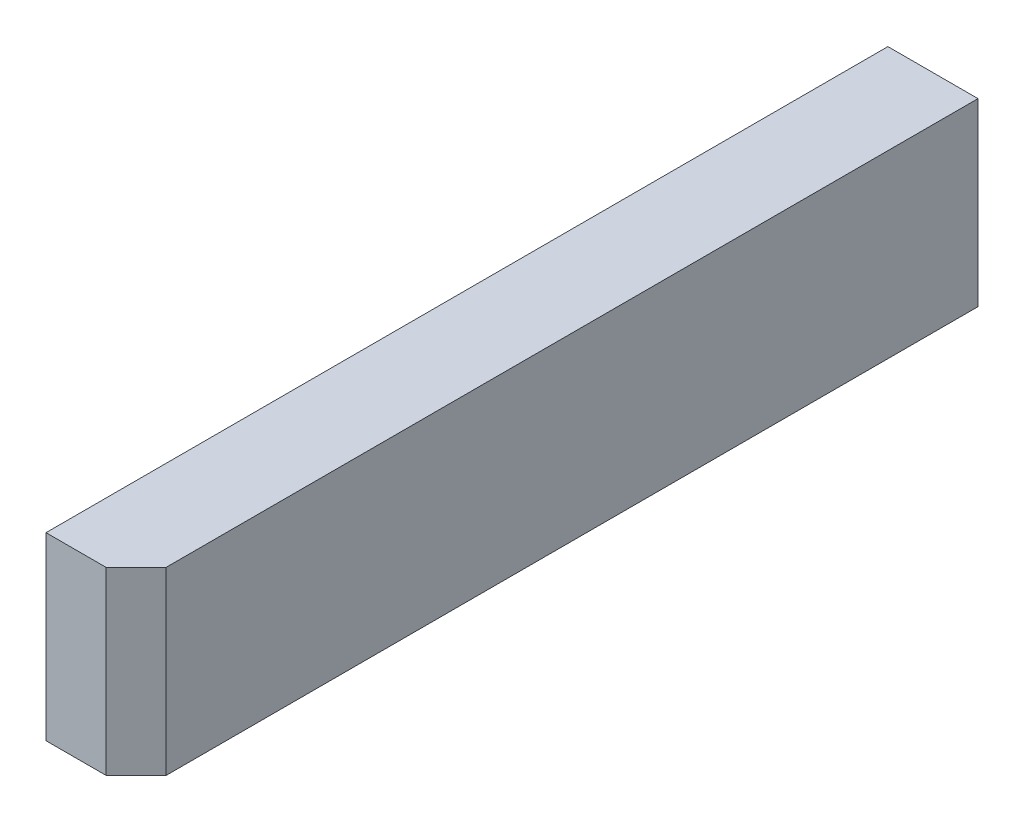
SolidWorks part; units mm, degrees
ref_plane "Front Plane" through (0, 0, 0) normal (0, 0, 1) x (1, 0, 0)
ref_plane "Top Plane" through (0, 0, 0) normal (0, 1, 0) x (1, 0, 0)
ref_plane "Right Plane" through (0, 0, 0) normal (1, 0, 0) x (0, 0, -1)
sketch "Sketch1" plane through (0, 0, 0) normal (1, 0, 0) x (0, 0, -1)
  line L5 (-89, -19.05) -> (89, -19.05)
  line L6 (-89, -19.05) -> (-89, 19.05)
  line L7 (-89, 19.05) -> (89, 19.05)
  line L8 (89, -19.05) -> (89, 19.05)
  line L9 (-89, -19.05) -> (89, 19.05) construction
  line L10 (-89, 19.05) -> (89, -19.05) construction
  point P0 (0, 0)
  dimension "D1" = 178
  dimension "D2" = 38.1
extrude "Boss-Extrude1" add sketch "Sketch1" along normal blind 19.05 contours L7 L8 L5 L6
chamfer "Chamfer1" distance 6.35 angle 45 1 edges at (19.05, 0, 89)
sketch "Sketch2" plane through (19.05, 0, 0) normal (1, 0, 0) x (0, 0, -1)
  point P0 (-14.3318, 0)
  point P2 (41.2261, 0)
